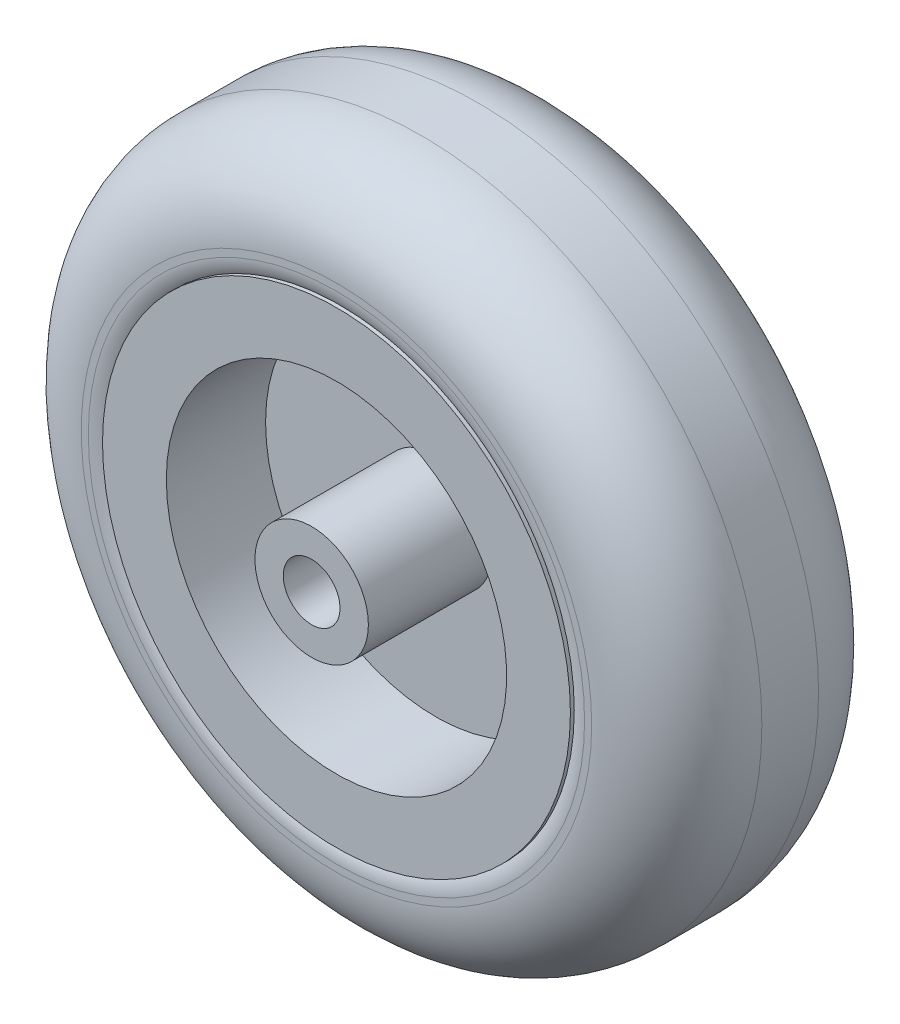
SolidWorks part; units mm, degrees
ref_plane "Front Plane" through (0, 0, 0) normal (0, 0, 1) x (1, 0, 0)
ref_plane "Top Plane" through (0, 0, 0) normal (0, 1, 0) x (1, 0, 0)
ref_plane "Right Plane" through (0, 0, 0) normal (1, 0, 0) x (0, 0, -1)
sketch "Sketch1" plane through (0, 0, 0) normal (0, 0, 1) x (1, 0, 0)
  circle A0 centre (0, 0) radius 76.2
  circle A1 centre (0, 0) radius 49.2125
  dimension "D1" = 152.4
  dimension "D2" = 98.425
extrude "Boss-Extrude1" add sketch "Sketch1" along normal mid plane 50.8
fillet "Fillet1" radius 19.05 2 edges at (76.2, 0, -25.4) (76.2, 0, 25.4)
fillet "Fillet2" radius 6.35 2 edges at (49.2125, 0, -25.4) (49.2125, 0, 25.4)
sketch "Sketch2" plane through (0, 0, 0) normal (0, 0, 1) x (1, 0, 0)
  circle A0 centre (0, 0) radius 52.3875
  dimension "D1" = 104.775
extrude "Boss-Extrude2" add sketch "Sketch2" along normal mid plane 50.8 separate body
sketch "Sketch3" plane through (0, 0, 0) normal (1, 0, 0) x (0, 0, -1)
  line L0 (0, 0) -> (130.4604, 0) construction
  line L1 (-22.225, 52.3875) -> (-22.225, 44.45)
  line L3 (-22.225, 44.45) -> (22.225, 44.45)
  line L4 (22.225, 44.45) -> (22.225, 52.3875)
  line L5 (22.225, 52.3875) -> (-22.225, 52.3875)
  line L6 (25.4, -52.3875) -> (-25.4, -52.3875)
  line L7 (-25.4, 52.3875) -> (25.4, 52.3875)
  line L8 (-25.4, 52.3875) -> (25.4, 52.3875) construction
  line L9 (25.4, -52.3875) -> (-25.4, -52.3875) construction
  line L10 (0, 44.45) -> (0, 0) construction
  dimension "D1" = 44.45
  dimension "D2" = 88.9
revolve "Cut-Revolve1" cut sketch "Sketch3" angle 360 about L0
sketch "Sketch4" plane through (0, 0, -25.4) normal (0, 0, -1) x (-1, 0, 0)
  circle A0 centre (0, 0) radius 38.1
  circle A1 centre (0, 0) radius 12.7
  dimension "D1" = 25.4
  dimension "D2" = 76.2
extrude "Cut-Extrude1" cut sketch "Sketch4" against normal blind 22.225
mirror "Mirror1" about plane through (0, 0, 0) normal (0, 0, 1) of "Cut-Extrude1"
sketch "Sketch5" plane through (0, 0, 0) normal (0, 0, 1) x (1, 0, 0)
  circle A0 centre (0, 0) radius 12.7
  circle A1 centre (0, 0) radius 12.7 construction
extrude "Boss-Extrude3" add sketch "Sketch5" along normal mid plane 61.9125
sketch "Sketch6" plane through (0, 0, -30.9562) normal (0, 0, -1) x (-1, 0, 0)
  circle A0 centre (0, 0) radius 6.35
  dimension "D1" = 12.7
extrude "Cut-Extrude2" cut sketch "Sketch6" against normal through all
